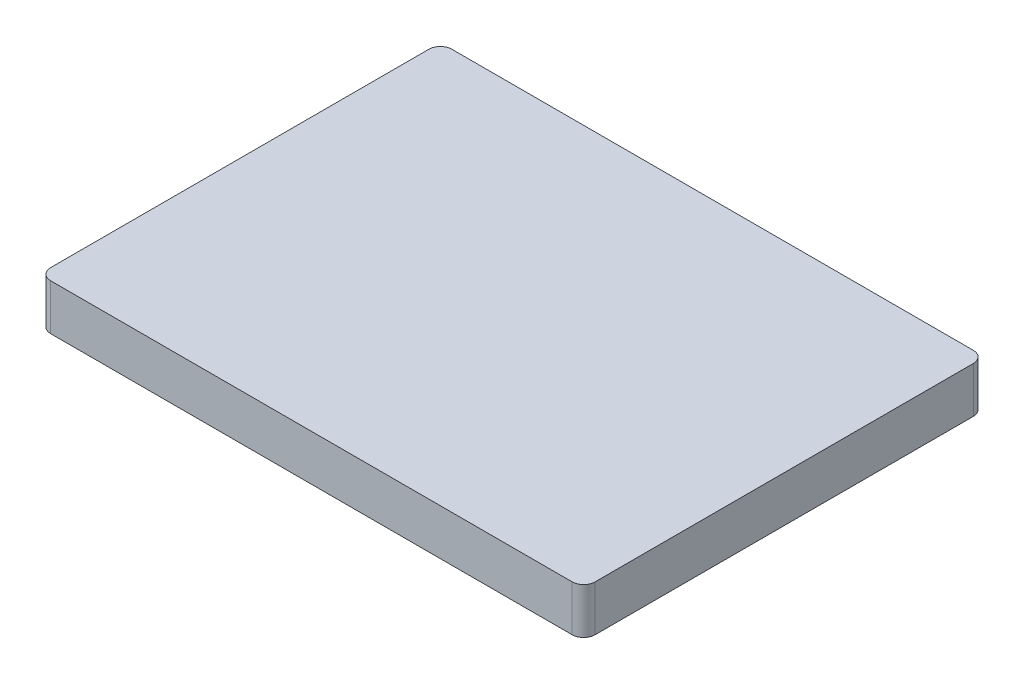
SolidWorks part; units mm, degrees
ref_plane "前基準面" through (0, 0, 0) normal (0, 0, 1) x (1, 0, 0)
ref_plane "上基準面" through (0, 0, 0) normal (0, 1, 0) x (1, 0, 0)
ref_plane "右基準面" through (0, 0, 0) normal (1, 0, 0) x (0, 0, -1)
sketch "草圖1" plane through (0, 0, 0) normal (0, 1, 0) x (1, 0, 0)
  line L0 (2, 0) -> (93, 0)
  line L1 (95, 2) -> (95, 68)
  line L2 (93, 70) -> (2, 70)
  line L3 (0, 68) -> (0, 2)
  arc A0 (0, 68) -> (2, 70) centre (2, 68) cw
  arc A1 (93, 70) -> (95, 68) centre (93, 68) cw
  arc A2 (95, 2) -> (93, 0) centre (93, 2) cw
  arc A3 (0, 2) -> (2, 0) centre (2, 2) ccw
  point P9 (95, 70)
  point P12 (95, 0)
  point P15 (0, 0)
  dimension "D3" = 2
  dimension "D1" = 95
  dimension "D2" = 70
extrude "填料-伸長1" add sketch "草圖1" along normal blind 8
